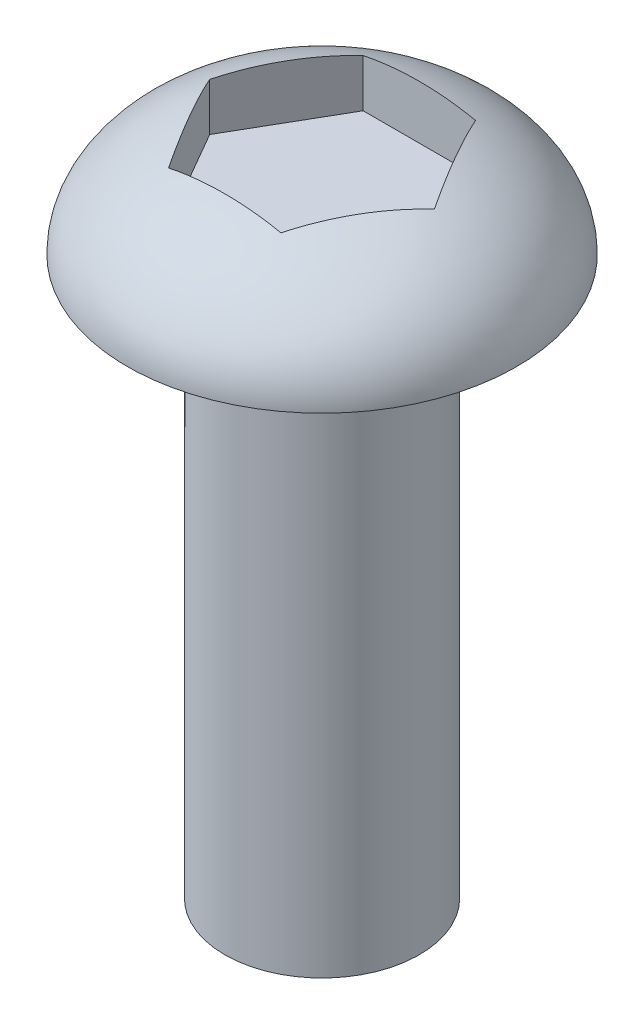
SolidWorks part; units mm, degrees
ref_plane "Front Plane" through (0, 0, 0) normal (0, 0, 1) x (1, 0, 0)
ref_plane "Top Plane" through (0, 0, 0) normal (0, 1, 0) x (1, 0, 0)
ref_plane "Right Plane" through (0, 0, 0) normal (1, 0, 0) x (0, 0, -1)
sketch "Sketch1" plane through (0, 0, 0) normal (0, 1, 0) x (1, 0, 0)
  circle A0 centre (0, 0) radius 2.5
  dimension "D1" = 5
extrude "Boss-Extrude1" add sketch "Sketch1" along normal blind 14.334
cosmetic thread "Cosmetic Thread2" parameters "D2"=3.5662
sketch "Sketch2" plane through (0, 0, 0) normal (1, 0, 0) x (0, 0, -1)
  line L0 (0, 14.334) -> (5, 14.334)
  line L1 (2.5, 14.334) -> (-2.5, 14.334) construction
  line L2 (0, 14.334) -> (0, 17.334)
  ellipse E0 centre (0, 14.334) end of major axis (5, 14.334) minor radius 3 (5, 14.334) -> (0, 17.334) ccw
  dimension "D1" = 5
  dimension "D2" = 3
revolve "Revolve1" add sketch "Sketch2" angle 360 about L2
cosmetic thread "Cosmetic Thread3" parameters "D2"=3.5662
sketch "Sketch3" plane through (0, 0, 0) normal (1, 0, 0) x (0, 0, -1)
  ellipse E0 centre (0, 14.334) end of major axis (5, 14.334) minor radius 3 (5, 14.334) -> (0, 17.334) ccw construction
  ellipse E1 centre (0, 14.334) end of major axis (5, 14.334) minor radius 3 (5, 14.334) -> (0, 17.334) ccw
  point P1 (0, 0)
  point P13 (0, 0)
ref_plane "Plane1" through (0, 17.334, 0) normal (0, 1, 0) x (1, 0, 0)
sketch "Sketch4" plane through (0, 17.334, 0) normal (0, 1, 0) x (1, 0, 0)
  line L1 (2.8868, 0) -> (1.4434, 2.5)
  line L2 (1.4434, 2.5) -> (-1.4434, 2.5)
  line L3 (-1.4434, 2.5) -> (-2.8868, 0)
  line L4 (-2.8868, 0) -> (-1.4434, -2.5)
  line L5 (-1.4434, -2.5) -> (1.4434, -2.5)
  line L6 (1.4434, -2.5) -> (2.8868, 0)
  circle A0 centre (0, 0) radius 2.5 construction
  point P10 (0, 2.5)
  dimension "D1" = 5
extrude "Cut-Extrude1" cut sketch "Sketch4" against normal blind 1.778
